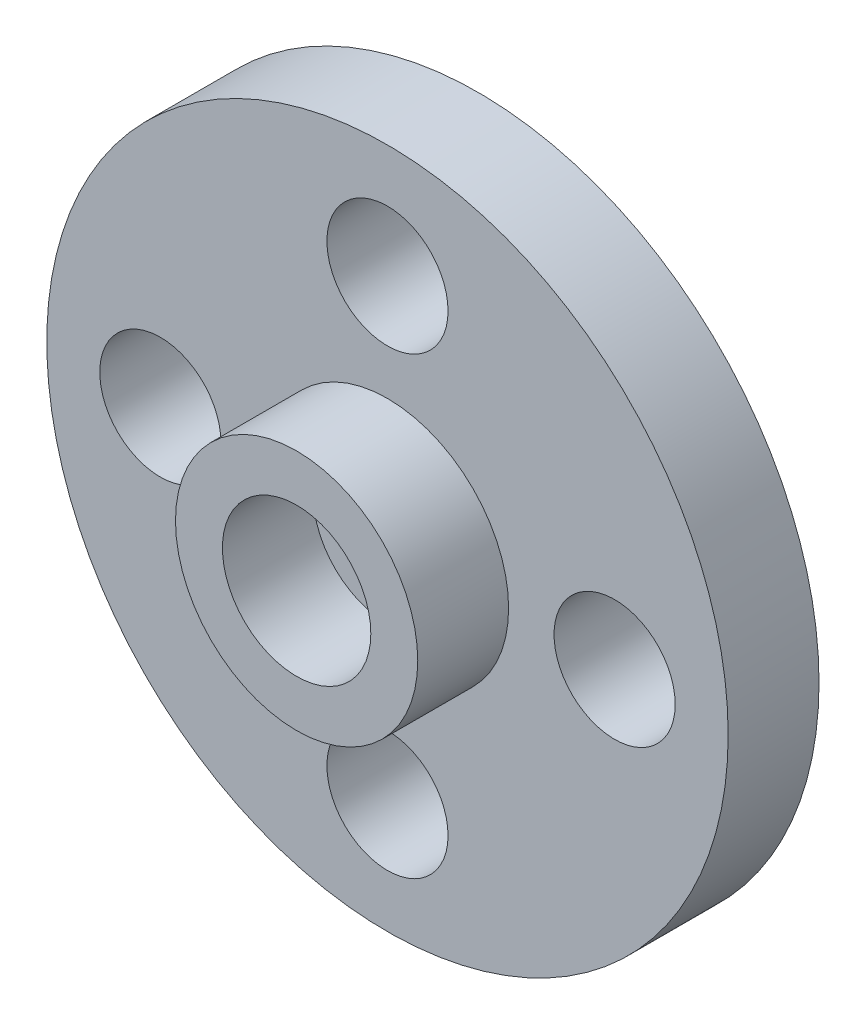
SolidWorks part; units mm, degrees
ref_plane "Ebene vorne" through (0, 0, 0) normal (0, 0, 1) x (1, 0, 0)
ref_plane "Ebene oben" through (0, 0, 0) normal (0, 1, 0) x (1, 0, 0)
ref_plane "Ebene rechts" through (0, 0, 0) normal (1, 0, 0) x (0, 0, -1)
sketch "Skizze1" plane through (0, 0, 0) normal (0, 0, 1) x (1, 0, 0)
  circle A0 centre (0, 0) radius 11.25
  dimension "D1" = 22.5
extrude "Aufsatz-Linear austragen1" add sketch "Skizze1" against normal blind 3
sketch "Skizze2" plane through (0, 0, 0) normal (0, 0, 1) x (1, 0, 0)
  circle A0 centre (0, 0) radius 4
  circle A1 centre (0, 0) radius 2.45
  dimension "D1" = 4.9
  dimension "D2" = 8
extrude "Aufsatz-Linear austragen2" add sketch "Skizze2" along normal blind 3
sketch "Skizze3" plane through (0, 0, 0) normal (0, 0, 1) x (1, 0, 0)
  circle A0 centre (0, 7.5) radius 2
  circle A1 centre (7.5, 0) radius 2
  circle A2 centre (0, -7.5) radius 2
  circle A3 centre (-7.5, 0) radius 2
  point P12 (0, 0)
  dimension "D1" = 4
  dimension "D3" = 4
  dimension "D2" = 7.5
extrude "Schnitt-Linear austragen1" cut sketch "Skizze3" against normal up to next
